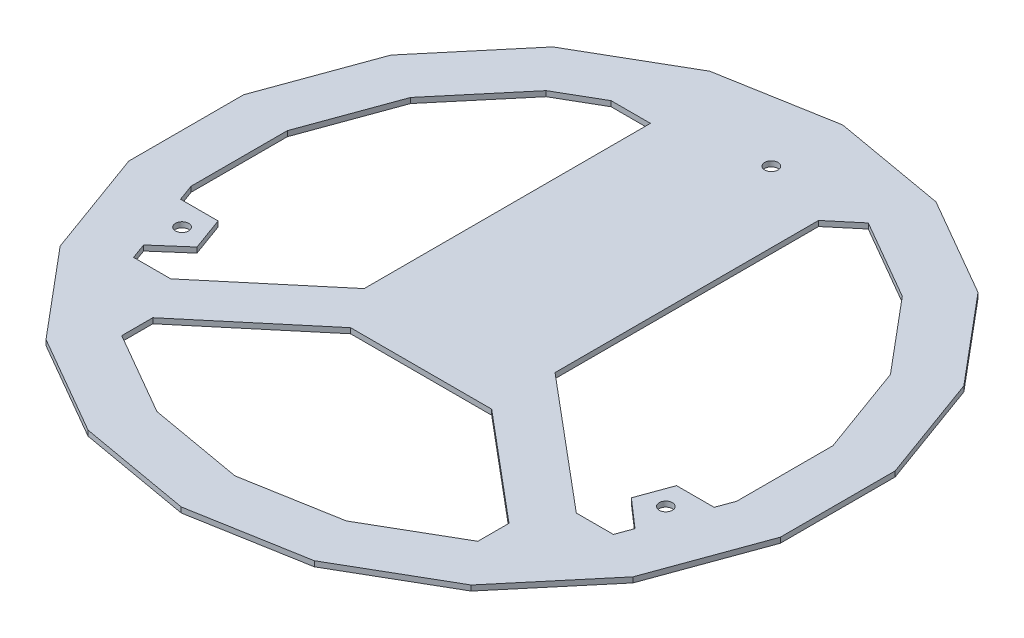
SolidWorks part; units mm, degrees
ref_plane "Front Plane" through (0, 0, 0) normal (0, 0, 1) x (1, 0, 0)
ref_plane "Top Plane" through (0, 0, 0) normal (0, 1, 0) x (1, 0, 0)
ref_plane "Right Plane" through (0, 0, 0) normal (1, 0, 0) x (0, 0, -1)
sketch "Sketch1" plane through (0, 0, 0) normal (0, 1, 0) x (1, 0, 0)
  line L1 (0, 75) -> (-25.6515, 70.4769)
  line L2 (-25.6515, 70.4769) -> (-48.2091, 57.4533)
  line L3 (-48.2091, 57.4533) -> (-64.9519, 37.5)
  line L4 (-64.9519, 37.5) -> (-73.8606, 13.0236)
  line L5 (-73.8606, 13.0236) -> (-73.8606, -13.0236)
  line L6 (-73.8606, -13.0236) -> (-64.9519, -37.5)
  line L7 (-64.9519, -37.5) -> (-48.2091, -57.4533)
  line L8 (-48.2091, -57.4533) -> (-25.6515, -70.4769)
  line L9 (-25.6515, -70.4769) -> (0, -75)
  line L10 (0, -75) -> (25.6515, -70.4769)
  line L11 (25.6515, -70.4769) -> (48.2091, -57.4533)
  line L12 (48.2091, -57.4533) -> (64.9519, -37.5)
  line L13 (64.9519, -37.5) -> (73.8606, -13.0236)
  line L14 (73.8606, -13.0236) -> (73.8606, 13.0236)
  line L15 (73.8606, 13.0236) -> (64.9519, 37.5)
  line L16 (64.9519, 37.5) -> (48.2091, 57.4533)
  line L17 (48.2091, 57.4533) -> (25.6515, 70.4769)
  line L18 (25.6515, 70.4769) -> (0, 75)
  line L19 (0, 62.8149) -> (-21.484, 59.0267)
  line L20 (-21.484, 59.0267) -> (-40.3766, 48.119)
  line L21 (-40.3766, 48.119) -> (-54.3993, 31.4074)
  line L22 (-54.3993, 31.4074) -> (-61.8606, 10.9077)
  line L23 (-61.8606, 10.9077) -> (-61.8606, -10.9077)
  line L24 (-61.8606, -10.9077) -> (-54.3993, -31.4074)
  line L25 (-54.3993, -31.4074) -> (-40.3766, -48.119)
  line L26 (-40.3766, -48.119) -> (-21.484, -59.0267)
  line L27 (-21.484, -59.0267) -> (0, -62.8149)
  line L28 (0, -62.8149) -> (21.484, -59.0267)
  line L29 (21.484, -59.0267) -> (40.3766, -48.119)
  line L30 (40.3766, -48.119) -> (54.3993, -31.4074)
  line L31 (54.3993, -31.4074) -> (61.8606, -10.9077)
  line L32 (61.8606, -10.9077) -> (61.8606, 10.9077)
  line L33 (61.8606, 10.9077) -> (54.3993, 31.4074)
  line L34 (54.3993, 31.4074) -> (40.3766, 48.119)
  line L35 (40.3766, 48.119) -> (21.484, 59.0267)
  line L36 (21.484, 59.0267) -> (0, 62.8149)
  circle A0 centre (0, 0) radius 73.8606 construction
  circle A1 centre (0, 0) radius 61.8606 construction
  point P1 (73.8606, 0)
  dimension "D1" = 150
  dimension "D2" = 12
extrude "Boss-Extrude1" add sketch "Sketch1" along normal blind 1.2
sketch "Sketch3" [suppressed] plane through (0, 1.6, 0) normal (0, 1, 0) x (1, 0, 0)
  line L0 (-73.8606, 13.0236) -> (-73.8606, -13.0236) construction
  line L1 (0, 62.8149) -> (-21.484, 59.0267)
  line L2 (-21.484, 59.0267) -> (-40.3766, 48.119)
  line L3 (-40.3766, 48.119) -> (-54.3993, 31.4074)
  line L4 (-54.3993, 31.4074) -> (-61.8606, 10.9077)
  line L5 (-61.8606, 10.9077) -> (-61.8606, -10.9077)
  line L6 (-61.8606, -10.9077) -> (-54.3993, -31.4074)
  line L7 (-54.3993, -31.4074) -> (-40.3766, -48.119)
  line L8 (-40.3766, -48.119) -> (-21.484, -59.0267)
  line L9 (-21.484, -59.0267) -> (0, -62.8149)
  line L10 (0, -62.8149) -> (21.484, -59.0267)
  line L11 (21.484, -59.0267) -> (40.3766, -48.119)
  line L12 (40.3766, -48.119) -> (54.3993, -31.4074)
  line L13 (54.3993, -31.4074) -> (61.8606, -10.9077)
  line L14 (61.8606, -10.9077) -> (61.8606, 10.9077)
  line L15 (61.8606, 10.9077) -> (54.3993, 31.4074)
  line L16 (54.3993, 31.4074) -> (40.3766, 48.119)
  line L17 (40.3766, 48.119) -> (21.484, 59.0267)
  line L18 (21.484, 59.0267) -> (0, 62.8149)
  line L19 (0, -98.3548) -> (33.6393, -92.4233)
  line L20 (33.6393, -92.4233) -> (63.2213, -75.3442)
  line L21 (63.2213, -75.3442) -> (85.1778, -49.1774)
  line L22 (85.1778, -49.1774) -> (96.8606, -17.0791)
  line L23 (96.8606, -17.0791) -> (96.8606, 17.0791)
  line L24 (96.8606, 17.0791) -> (85.1778, 49.1774)
  line L25 (85.1778, 49.1774) -> (63.2213, 75.3442)
  line L26 (63.2213, 75.3442) -> (33.6393, 92.4233)
  line L27 (33.6393, 92.4233) -> (0, 98.3548)
  line L28 (0, 98.3548) -> (-33.6393, 92.4233)
  line L29 (-33.6393, 92.4233) -> (-63.2213, 75.3442)
  line L30 (-63.2213, 75.3442) -> (-85.1778, 49.1774)
  line L31 (-85.1778, 49.1774) -> (-96.8606, 17.0791)
  line L32 (-96.8606, 17.0791) -> (-96.8606, -17.0791)
  line L33 (-96.8606, -17.0791) -> (-85.1778, -49.1774)
  line L34 (-85.1778, -49.1774) -> (-63.2213, -75.3442)
  line L35 (-63.2213, -75.3442) -> (-33.6393, -92.4233)
  line L36 (-33.6393, -92.4233) -> (0, -98.3548)
  circle A0 centre (0, 0) radius 61.8606 construction
  circle A1 centre (0, 0) radius 96.8606 construction
  dimension "D1" = 23
  dimension "D2" = 21.8154
sketch "Sketch15" plane through (0, 0, 0) normal (0, -1, 0) x (1, 0, 0)
  line L1 (0, -101.4011) -> (34.6812, -95.2859)
  line L2 (34.6812, -95.2859) -> (36.9303, -93.9874)
  line L4 (92.6205, -37.5) -> (99.8606, -17.6081)
  line L5 (99.8606, -17.6081) -> (99.8606, 17.6081)
  line L6 (99.8606, 17.6081) -> (92.6205, 37.5)
  line L13 (-92.6205, 37.5) -> (-99.8606, 17.6081)
  line L14 (-99.8606, 17.6081) -> (-99.8606, -17.6081)
  line L15 (-99.8606, -17.6081) -> (-92.6205, -37.5)
  line L17 (-36.9303, -93.9874) -> (-34.6812, -95.2859)
  line L18 (-34.6812, -95.2859) -> (0, -101.4011)
  line L19 (-36.9303, -84.7497) -> (-36.9303, -93.9874)
  line L20 (0, -93.2777) -> (31.9028, -87.6523)
  line L21 (31.9028, -87.6523) -> (36.9303, -84.7497)
  line L23 (84.1071, -37.5) -> (91.8606, -16.1975)
  line L24 (91.8606, -16.1975) -> (91.8606, 16.1975)
  line L25 (91.8606, 16.1975) -> (84.1071, 37.5)
  line L32 (-84.1071, 37.5) -> (-91.8606, 16.1975)
  line L33 (-91.8606, 16.1975) -> (-91.8606, -16.1975)
  line L34 (-91.8606, -16.1975) -> (-84.1071, -37.5)
  line L36 (-36.9303, -84.7497) -> (-31.9028, -87.6523)
  line L37 (-31.9028, -87.6523) -> (0, -93.2777)
  line L38 (-73.8606, -13.0236) -> (-73.8606, 13.0236) construction
  line L39 (84.1071, -37.5) -> (92.6205, -37.5)
  line L40 (-84.1071, -37.5) -> (-92.6205, -37.5)
  line L41 (-84.1071, 37.5) -> (-92.6205, 37.5)
  line L42 (84.1071, 37.5) -> (92.6205, 37.5)
  line L43 (36.9303, -84.7497) -> (36.9303, -93.9874)
  line L46 (76.4976, -64.1891) -> (87.8159, -50.7005) [skipped]
  line L47 (70.3693, -59.0468) -> (80.7808, -46.6388) [skipped]
  line L48 (70.3693, 59.0468) -> (59.9577, 71.4548) [skipped]
  line L49 (87.8159, 50.7005) -> (65.1794, 77.6777) [skipped]
  line L50 (-65.1794, 77.6777) -> (-76.4976, 64.1891) [skipped]
  line L51 (-59.9577, 71.4548) -> (-70.3693, 59.0468) [skipped]
  line L52 (-76.4976, -64.1891) -> (-65.1794, -77.6777) [skipped]
  line L53 (-70.3693, -59.0468) -> (-59.9577, -71.4548) [skipped]
  line L54 (-34.6812, 95.2859) -> (-49.9303, 86.4818) [skipped]
  line L55 (-31.9028, 87.6523) -> (-45.9303, 79.5536) [skipped]
  line L56 (0, 101.4011) -> (-17.3406, 98.3435) [skipped]
  line L57 (0, 93.2777) -> (-15.9514, 90.465) [skipped]
  line L58 (31.9028, 87.6523) -> (0, 93.2777) [skipped]
  line L59 (34.6812, 95.2859) -> (0, 101.4011) [skipped]
  line L60 (49.9303, 86.4818) -> (34.6812, 95.2859) [skipped]
  line L61 (45.9303, 79.5536) -> (31.9028, 87.6523) [skipped]
  arc A0 (92.5521, -37.5) -> (92.5521, 37.5) centre (0, 0) ccw construction
  arc A1 (83.8577, -37.5) -> (83.8577, 37.5) centre (0, 0) ccw construction
  arc A4 (-83.8577, 37.5) -> (-83.8577, -37.5) centre (0, 0) ccw construction
  arc A5 (-92.5521, 37.5) -> (-92.5521, -37.5) centre (0, 0) ccw construction
  arc A6 (-36.9303, -84.1102) -> (36.9303, -84.1102) centre (0, 0) ccw construction
  arc A7 (-36.9303, -92.7809) -> (36.9303, -92.7809) centre (0, 0) ccw construction
  dimension "D4" = 157.7183
  dimension "D1" = 99.8606
  dimension "D3" = 36.9303
  dimension "D2" = 8
extrude "Boss-Extrude17" add sketch "Sketch15" against normal up to surface (1.2 mm away) separate body up to face at (0, 1.2, 0)
sketch "Sketch18" plane through (0, 0, 0) normal (0, -1, 0) x (1, 0, 0)
  line L0 (-91.8606, 12.5) -> (-73.8606, 12.5)
  line L1 (-91.8606, -16.1975) -> (-91.8606, 16.1975) construction
  line L2 (-73.8606, -13.0236) -> (-73.8606, 13.0236) construction
  line L3 (-91.8606, -12.5) -> (-73.8606, -12.5)
  line L4 (73.8606, 12.5) -> (91.8606, 12.5)
  line L5 (73.8606, 13.0236) -> (73.8606, -13.0236) construction
  line L6 (91.8606, 16.1975) -> (91.8606, -16.1975) construction
  line L7 (73.8606, -12.5) -> (91.8606, -12.5)
  line L8 (-91.8606, 12.5) -> (-91.8606, -12.5)
  line L9 (-73.8606, -12.5) -> (-73.8606, 12.5)
  line L10 (73.8606, 12.5) -> (73.8606, -12.5)
  line L11 (91.8606, -12.5) -> (91.8606, 12.5)
  line L12 (-12.5, -72.7959) -> (-12.5, -91.0736)
  line L13 (0, -75) -> (-25.6515, -70.4769) construction
  line L14 (0, -93.2777) -> (-31.9028, -87.6523) construction
  line L15 (12.5, -72.7959) -> (12.5, -91.0736)
  line L16 (25.6515, -70.4769) -> (0, -75) construction
  line L17 (31.9028, -87.6523) -> (0, -93.2777) construction
  line L18 (-12.5, -72.7959) -> (0, -75)
  line L19 (0, -75) -> (12.5, -72.7959)
  line L20 (12.5, -91.0736) -> (0, -93.2777)
  line L21 (0, -93.2777) -> (-12.5, -91.0736)
  point P8 (-91.8606, 0)
  dimension "D1" = 25
  dimension "D2" = 12.5
  dimension "D3" = 25
  dimension "D4" = 12.5
extrude "Boss-Extrude18" add sketch "Sketch18" against normal up to surface (1.2 mm away) up to face at (0, 1.2, 0)
sketch "Sketch19" plane through (0, 0, 0) normal (0, -1, 0) x (1, 0, 0)
  line L0 (-91.8606, 16.1975) -> (-82.8606, 12.5)
  line L2 (-73.8606, 12.5) -> (-91.8606, 12.5) construction
  line L3 (-91.8606, -16.1975) -> (-82.8606, -12.5)
  line L4 (-91.8606, -12.5) -> (-73.8606, -12.5) construction
  line L5 (-82.8606, -12.5) -> (-91.8606, -12.5)
  line L6 (-91.8606, -12.5) -> (-91.8606, -16.1975)
  line L7 (-82.8606, 12.5) -> (-91.8606, 12.5)
  line L8 (-91.8606, 12.5) -> (-91.8606, 16.1975)
  line L9 (91.8606, 16.1975) -> (82.8606, 12.5)
  line L10 (91.8606, 12.5) -> (73.8606, 12.5) construction
  line L11 (82.8606, 12.5) -> (91.8606, 12.5)
  line L12 (91.8606, 12.5) -> (91.8606, 16.1975)
  line L13 (91.8606, -16.1975) -> (82.8606, -12.5)
  line L14 (73.8606, -12.5) -> (91.8606, -12.5) construction
  line L15 (82.8606, -12.5) -> (91.8606, -12.5)
  line L16 (91.8606, -12.5) -> (91.8606, -16.1975)
  line L17 (22.2014, -89.363) -> (12.5, -81.9348)
  line L18 (31.9028, -87.6523) -> (12.5, -91.0736) construction
  line L19 (12.5, -91.0736) -> (12.5, -72.7959) construction
  line L20 (12.5, -81.9348) -> (12.5, -91.0736)
  line L21 (12.5, -91.0736) -> (22.2014, -89.363)
  line L22 (-12.5, -81.9348) -> (-12.5, -91.0736)
  line L23 (-12.5, -72.7959) -> (-12.5, -91.0736) construction
  line L24 (-12.5, -91.0736) -> (-22.2014, -89.363)
  line L25 (-12.5, -91.0736) -> (-31.9028, -87.6523) construction
  line L26 (-22.2014, -89.363) -> (-12.5, -81.9348)
extrude "Boss-Extrude19" add sketch "Sketch19" against normal up to surface (1.2 mm away) up to face at (0, 1.2, -19.9535)
sketch "Sketch20" plane through (0, 0, 0) normal (0, -1, 0) x (1, 0, 0)
  line L0 (-36.9303, 63.9651) -> (-36.9303, 91.9651)
  line L1 (-48.2091, 57.4533) -> (-25.6515, 70.4769) construction
  line L2 (-36.9303, 91.9651) -> (-32.0524, 91.9651)
  line L3 (-32.0524, 91.9651) -> (-12.8258, 72.7385)
  line L4 (-25.6515, 70.4769) -> (0, 75) construction
  line L6 (25.6515, 70.4769) -> (48.2091, 57.4533) construction
  line L7 (36.9303, 63.9651) -> (36.9303, 91.9651)
  line L8 (36.9303, 91.9651) -> (32.0524, 91.9651)
  line L9 (32.0524, 91.9651) -> (12.8258, 72.7385)
  line L10 (0, 75) -> (25.6515, 70.4769) construction
  line L11 (12.8258, 72.7385) -> (25.6515, 70.4769)
  line L12 (25.6515, 70.4769) -> (36.9303, 63.9651)
  line L13 (-12.8258, 72.7385) -> (-25.6515, 70.4769)
  line L14 (-25.6515, 70.4769) -> (-36.9303, 63.9651)
  dimension "D1" = 135
  dimension "D2" = 135
  dimension "D3" = 28
  dimension "D4" = 28
extrude "Boss-Extrude20" add sketch "Sketch20" against normal up to surface (1.2 mm away) up to face at (0, 1.2, -22.1061)
sketch "Sketch23" plane through (0, 1.2, 0) normal (0, 1, 0) x (1, 0, 0)
  line L0 (-92.6205, 37.5) -> (-80.6205, 37.5)
  line L1 (-80.6205, 37.5) -> (-88.8275, 14.9514)
  line L2 (-91.8606, 16.1975) -> (-82.8606, 12.5) construction
  line L3 (-92.6205, -37.5) -> (-80.6205, -37.5)
  line L4 (-80.6205, -37.5) -> (-88.8275, -14.9514)
  line L5 (-82.8606, -12.5) -> (-91.8606, -16.1975) construction
  line L8 (-99.8606, 17.6081) -> (-92.6205, 37.5) construction
  line L9 (-92.6205, -37.5) -> (-99.8606, -17.6081) construction
  line L10 (-92.6205, 37.5) -> (-99.8606, 17.6081)
  line L11 (-99.8606, 17.6081) -> (-99.8606, -17.6081)
  line L12 (-99.8606, -17.6081) -> (-92.6205, -37.5)
  line L13 (-88.8275, -14.9514) -> (-88.8275, 14.9514)
  line L14 (0, 62.8149) -> (0, -62.8149) construction
  line L15 (80.6205, -37.5) -> (88.8275, -14.9514)
  line L16 (92.6205, -37.5) -> (80.6205, -37.5)
  line L17 (99.8606, -17.6081) -> (92.6205, -37.5)
  line L18 (99.8606, 17.6081) -> (99.8606, -17.6081)
  line L19 (92.6205, 37.5) -> (99.8606, 17.6081)
  line L20 (92.6205, 37.5) -> (80.6205, 37.5)
  line L21 (80.6205, 37.5) -> (88.8275, 14.9514)
  line L22 (88.8275, -14.9514) -> (88.8275, 14.9514)
  dimension "D1" = 12
  dimension "D2" = 12
extrude "Boss-Extrude21" [suppressed] add sketch "Sketch23" against normal up to surface (1.2 mm away)
sketch "Sketch24" plane through (0, 1.2, 0) normal (0, 1, 0) x (1, 0, 0)
  line L0 (-36.9303, 93.9874) -> (-36.9303, 80.1309)
  line L1 (-36.9303, 80.1309) -> (-30.5137, 83.8356)
  line L3 (-30.5137, 83.8356) -> (-17.8897, 86.0615)
  line L5 (-12.5, 81.9348) -> (-22.2014, 89.363) construction
  line L7 (-36.9303, 93.9874) -> (-34.6812, 95.2859) construction
  line L8 (-34.6812, 95.2859) -> (0, 101.4011) construction
  line L9 (-36.9303, 93.9874) -> (-34.6812, 95.2859)
  line L10 (-34.6812, 95.2859) -> (0, 101.4011)
  line L11 (0, 101.4011) -> (34.6812, 95.2859)
  line L12 (34.6812, 95.2859) -> (36.9303, 93.9874)
  line L13 (36.9303, 93.9874) -> (36.9303, 80.1309)
  line L14 (36.9303, 80.1309) -> (30.5137, 83.8356)
  line L16 (30.5137, 83.8356) -> (17.8897, 86.0615)
  line L18 (22.2014, 89.363) -> (12.5, 81.9348) construction
  line L19 (-17.8897, 86.0615) -> (17.8897, 86.0615)
  dimension "D1" = 12
  dimension "D2" = 12
  dimension "D3" = 12
  dimension "D4" = 12
extrude "Boss-Extrude22" add sketch "Sketch24" against normal up to surface (1.2 mm away) up to face at (0, 0, -11.8972)
sketch "Sketch27" plane through (0, 0, 0) normal (0, -1, 0) x (1, 0, 0)
  line L2 (-50.9233, 35.55) -> (-43.8526, 43.9765)
  line L23 (43.8526, 43.9765) -> (50.9233, 35.55)
  line L26 (-16, 20.6053) -> (16, 20.6053)
  line L27 (-16, -59.9936) -> (0, -62.8149)
  line L29 (0, -62.8149) -> (16, -59.9936)
  line L38 (-47.388, 39.7632) -> (-56.5805, 47.4767) construction
  line L40 (-54.3993, 31.4074) -> (-40.3766, 48.119) construction
  line L41 (-64.9519, 37.5) -> (-48.2091, 57.4533) construction
  line L42 (47.388, 39.7632) -> (56.5805, 47.4767) construction
  line L43 (40.3766, 48.119) -> (54.3993, 31.4074) construction
  line L44 (48.2091, 57.4533) -> (64.9519, 37.5) construction
  line L45 (-16, 6.2459) -> (-16, -59.9936)
  line L48 (0, -62.8149) -> (-21.484, -59.0267) construction
  line L49 (16, 6.2459) -> (16, -59.9936)
  line L51 (21.484, -59.0267) -> (0, -62.8149) construction
  line L52 (-43.8526, 43.9765) -> (-16, 20.6053)
  line L53 (-50.9233, 35.55) -> (-16, 6.2459)
  line L54 (16, 20.6053) -> (43.8526, 43.9765)
  line L55 (50.9233, 35.55) -> (16, 6.2459)
  dimension "D1" = 32
  dimension "D2" = 16
  dimension "D3" = 5.5
  dimension "D4" = 5.5
  dimension "D5" = 11
  dimension "D6" = 11
  dimension "D7" = 32
extrude "Boss-Extrude26" add sketch "Sketch27" against normal up to surface (1.2 mm away) up to face at (0, 1.2, -11.5186)
sketch "Sketch34" plane through (0, 1.2, 0) normal (0, 1, 0) x (1, 0, 0)
  line L6 (0, 0) -> (0, -75) construction
  line L9 (-58.1299, -21.1576) -> (-50.6124, -18.4214) construction
  line L10 (-61.8606, -10.9077) -> (-54.3993, -31.4074) construction
  line L26 (-60.4939, -14.6626) -> (-55.7056, -27.8183)
  line L32 (-50.6124, -18.4214) -> (-49.2443, -22.1802)
  line L33 (-49.2443, -22.1802) -> (-55.7056, -27.8183)
  line L34 (-50.6124, -18.4214) -> (-51.9805, -14.6626)
  line L35 (-51.9805, -14.6626) -> (-60.4939, -14.6626)
  line L36 (50.6124, -18.4214) -> (49.2443, -22.1802)
  line L37 (49.2443, -22.1802) -> (55.7056, -27.8183)
  line L38 (60.4939, -14.6626) -> (55.7056, -27.8183)
  line L39 (51.9805, -14.6626) -> (60.4939, -14.6626)
  line L40 (50.6124, -18.4214) -> (51.9805, -14.6626)
  dimension "D1" = 8
  dimension "D2" = 14
  dimension "D3" = 4
  dimension "D4" = 8
sketch "Sketch37" plane through (0, 1.2, 0) normal (0, 1, 0) x (1, 0, 0)
  line L1 (-54.8481, 19.9631) -> (54.8481, 19.9631) construction
  line L2 (-54.8481, 19.9631) -> (-54.8481, -19.9631) construction
  line L3 (-54.8481, -19.9631) -> (54.8481, -19.9631) construction
  line L4 (54.8481, 19.9631) -> (54.8481, -19.9631) construction
  line L5 (-54.8481, 19.9631) -> (54.8481, -19.9631) construction
  line L6 (-54.8481, -19.9631) -> (54.8481, 19.9631) construction
  circle A0 centre (-54.8481, -19.9631) radius 1.5
  circle A1 centre (54.8481, -19.9631) radius 1.5
  point P0 (0, 0)
  dimension "D3" = 3
  dimension "D4" = 3
  dimension "D1" = 109.6963
  dimension "D2" = 39.9262
sketch "Sketch38" plane through (0, 1.2, 0) normal (0, 1, 0) x (1, 0, 0)
  line L0 (0, 0) -> (0, 58.812) construction
  circle A0 centre (0, 58.812) radius 1.5
  dimension "D2" = 3
  dimension "D1" = 58.812
sketch "Sketch43" plane through (0, 0, 0) normal (0, -1, 0) x (1, 0, 0)
  line L0 (-40.3766, 48.119) -> (-40.3766, 41.0598)
  line L1 (-16, 20.6053) -> (-43.8526, 43.9765) construction
  line L2 (40.3766, 48.119) -> (40.3766, 41.0598)
  line L3 (43.8526, 43.9765) -> (16, 20.6053) construction
  line L4 (54.3993, 31.4074) -> (45.9864, 31.4074)
  line L5 (16, 6.2459) -> (50.9233, 35.55) construction
  line L6 (45.9864, 31.4074) -> (50.9233, 35.55)
  line L7 (50.9233, 35.55) -> (54.3993, 31.4074)
  line L8 (40.3766, 48.119) -> (43.8526, 43.9765)
  line L9 (43.8526, 43.9765) -> (40.3766, 41.0598)
  line L10 (-40.3766, 41.0598) -> (-43.8526, 43.9765)
  line L11 (-43.8526, 43.9765) -> (-40.3766, 48.119)
  line L12 (-54.3993, 31.4074) -> (-45.9864, 31.4074)
  line L13 (-50.9233, 35.55) -> (-16, 6.2459) construction
  line L14 (-45.9864, 31.4074) -> (-50.9233, 35.55)
  line L15 (-50.9233, 35.55) -> (-54.3993, 31.4074)
  line L41 (-22.1284, -58.6546) -> (-16, -53.5123)
  line L42 (-21.484, -59.0267) -> (-40.3766, -48.119) construction
  line L43 (-16, 6.2459) -> (-16, -59.9936) construction
  line L44 (-16, -53.5123) -> (-16, -59.9936)
  line L45 (-16, -59.9936) -> (-21.484, -59.0267)
  line L46 (-21.484, -59.0267) -> (-22.1284, -58.6546)
  line L47 (16, -59.9936) -> (16, -53.5123)
  line L48 (16, -59.9936) -> (16, 6.2459) construction
  line L49 (16, -53.5123) -> (22.1284, -58.6546)
  line L50 (40.3766, -48.119) -> (21.484, -59.0267) construction
  line L51 (22.1284, -58.6546) -> (21.484, -59.0267)
  line L52 (21.484, -59.0267) -> (16, -59.9936)
  line L53 (16, 20.6053) -> (-16, 20.6053) construction
  dimension "D1" = 40
  dimension "D2" = 40
  dimension "D3" = 8
  dimension "D4" = 8
extrude "Boss-Extrude28" add sketch "Sketch43" against normal up to surface (1.2 mm away) up to face at (41.9226, 1.2, -13.9271)
sketch "Sketch26" plane through (0, 1.2, 0) normal (0, 1, 0) x (1, 0, 0)
  line L0 (-36.9303, 93.9874) -> (-45.9303, 88.7912)
  line L1 (-45.9303, 88.7912) -> (-45.9303, 74.9348)
  line L2 (-45.9303, 74.9348) -> (-36.9303, 80.1309)
  line L3 (36.9303, 93.9874) -> (45.9303, 88.7912)
  line L4 (45.9303, 88.7912) -> (45.9303, 74.9348)
  line L5 (45.9303, 74.9348) -> (36.9303, 80.1309)
  line L6 (30.5137, 83.8356) -> (36.9303, 80.1309) construction
  line L7 (-36.9303, 80.1309) -> (-30.5137, 83.8356) construction
  line L8 (-36.9303, 80.1309) -> (-36.9303, 93.9874) construction
  line L9 (36.9303, 93.9874) -> (36.9303, 80.1309) construction
  line L10 (36.9303, 80.1309) -> (36.9303, 93.9874)
  line L11 (-36.9303, 80.1309) -> (-36.9303, 93.9874)
  dimension "D1" = 9
  dimension "D2" = 9
extrude "Boss-Extrude23" add sketch "Sketch26" against normal up to surface (1.2 mm away) up to face at (41.4457, 0, -13.6259)
extrude "Cut-Extrude2" cut sketch "Sketch38" against normal up to surface (1.2 mm away) up to face at (41.4457, 0, -13.6259)
extrude "Boss-Extrude29" add sketch "Sketch34" against normal up to surface (1.2 mm away) up to face at (0, 0, -57.312)
extrude "Cut-Extrude3" cut sketch "Sketch37" against normal up to surface (1.2 mm away) up to face at (0, 0, -57.312)
sketch "Sketch44" plane through (0, 0, 0) normal (0, -1, 0) x (1, 0, 0)
  line L1 (-45.9864, 31.4074) -> (-16, 6.2459) construction
  line L2 (-22.1284, 11.3882) -> (-16, 6.2459)
  line L3 (-16, 6.2459) -> (-16, -53.5123)
  line L4 (-16, -53.5123) -> (-22.1284, -58.6546)
  line L5 (-22.1284, 11.3882) -> (-22.1284, -53.5123)
  line L7 (-22.1284, -58.6546) -> (-31.0351, -53.5123)
  line L9 (-22.1284, -53.5123) -> (-31.0351, -53.5123)
  line L10 (-22.1284, -58.6546) -> (-40.3766, -48.119) construction
  dimension "D1" = 8.9067
extrude "Boss-Extrude30" add sketch "Sketch44" against normal up to surface (1.2 mm away) up to face at (-54.8481, 1.2, 21.4631)
sketch "Sketch46" plane through (0, 0, 0) normal (0, -1, 0) x (1, 0, 0)
  line L0 (-73.8606, -13.0236) -> (-84.1071, -37.5)
  line L1 (-84.1071, -37.5) -> (-92.6205, -37.5)
  line L2 (-92.6205, -37.5) -> (-99.8606, -17.6081)
  line L3 (-99.8606, -17.6081) -> (-99.8606, 17.6081)
  line L4 (-92.6205, 37.5) -> (-99.8606, 17.6081) construction
  line L5 (-99.8606, 17.6081) -> (-92.6205, 37.5)
  line L6 (-92.6205, 37.5) -> (-84.1071, 37.5)
  line L7 (-84.1071, 37.5) -> (-73.8606, 12.5)
  line L8 (-73.8606, 12.5) -> (-73.8606, -13.0236)
  line L9 (73.8606, 12.5) -> (84.1071, 37.5)
  line L10 (84.1071, 37.5) -> (92.6205, 37.5)
  line L11 (92.6205, 37.5) -> (99.8606, 17.6081)
  line L12 (99.8606, 17.6081) -> (99.8606, -17.6081)
  line L13 (99.8606, -17.6081) -> (92.6205, -37.5)
  line L14 (92.6205, -37.5) -> (84.1071, -37.5)
  line L15 (84.1071, -37.5) -> (73.8606, -12.5)
  line L16 (73.8606, -12.5) -> (73.8606, 12.5)
  line L18 (-12.5, -72.7959) -> (-45.9303, -74.9348)
  line L19 (-45.9303, -74.9348) -> (-45.9303, -88.7912)
  line L20 (-45.9303, -88.7912) -> (-34.6812, -95.2859)
  line L21 (-34.6812, -95.2859) -> (0, -101.4011)
  line L22 (0, -101.4011) -> (34.6812, -95.2859)
  line L23 (34.6812, -95.2859) -> (45.9303, -88.7912)
  line L24 (45.9303, -88.7912) -> (45.9303, -74.9348)
  line L25 (45.9303, -74.9348) -> (12.5, -72.7959)
  line L26 (-36.9303, 63.9651) -> (-36.9303, 91.9651)
  line L27 (-12.5, -72.7959) -> (0, -75)
  line L28 (0, -75) -> (12.5, -72.7959)
  line L29 (-36.9303, 63.9651) -> (-25.6515, 70.4769)
  line L31 (-36.9303, 91.9651) -> (-32.0524, 91.9651)
  line L32 (-32.0524, 91.9651) -> (-12.8258, 72.7385)
  line L34 (12.8258, 72.7385) -> (32.0524, 91.9651)
  line L35 (12.8258, 72.7385) -> (25.6515, 70.4769)
  line L37 (32.0524, 91.9651) -> (36.9303, 91.9651)
  line L38 (36.9303, 63.9651) -> (25.6515, 70.4769)
  line L40 (-12.8258, 72.7385) -> (-25.6515, 70.4769)
  line L42 (36.9303, 91.9651) -> (36.9303, 63.9651)
  dimension "D1" = 160
  dimension "D2" = 160
  dimension "D3" = 160
  dimension "D4" = 13.0236
  dimension "D5" = 13.0236
extrude "Cut-Extrude4" cut sketch "Sketch46" against normal up to surface (1.2 mm away) up to face at (-47.0461, 1.2, -2.5403)
